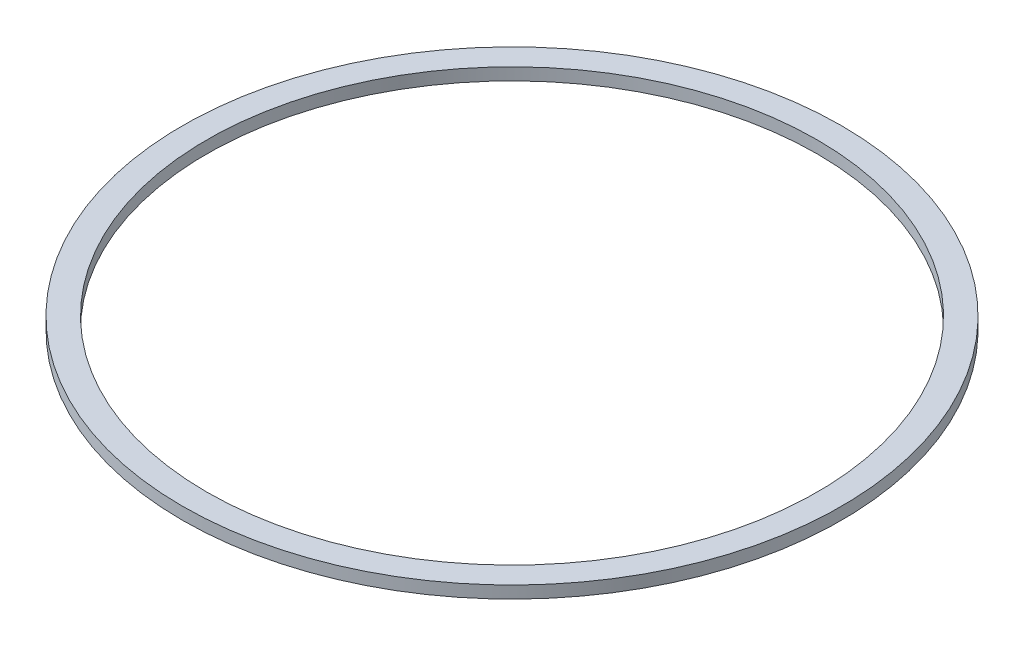
SolidWorks part; units mm, degrees
ref_plane "Front Plane" through (0, 0, 0) normal (0, 0, 1) x (1, 0, 0)
ref_plane "Top Plane" through (0, 0, 0) normal (0, 1, 0) x (1, 0, 0)
ref_plane "Right Plane" through (0, 0, 0) normal (1, 0, 0) x (0, 0, -1)
sketch "Sketch1" plane through (0, 0, 0) normal (0, 1, 0) x (1, 0, 0)
  circle A0 centre (0, 0) radius 25
  circle A1 centre (0, 0) radius 27
  dimension "D1" = 50
  dimension "D2" = 2
extrude "Boss-Extrude1" add sketch "Sketch1" along normal blind 1
